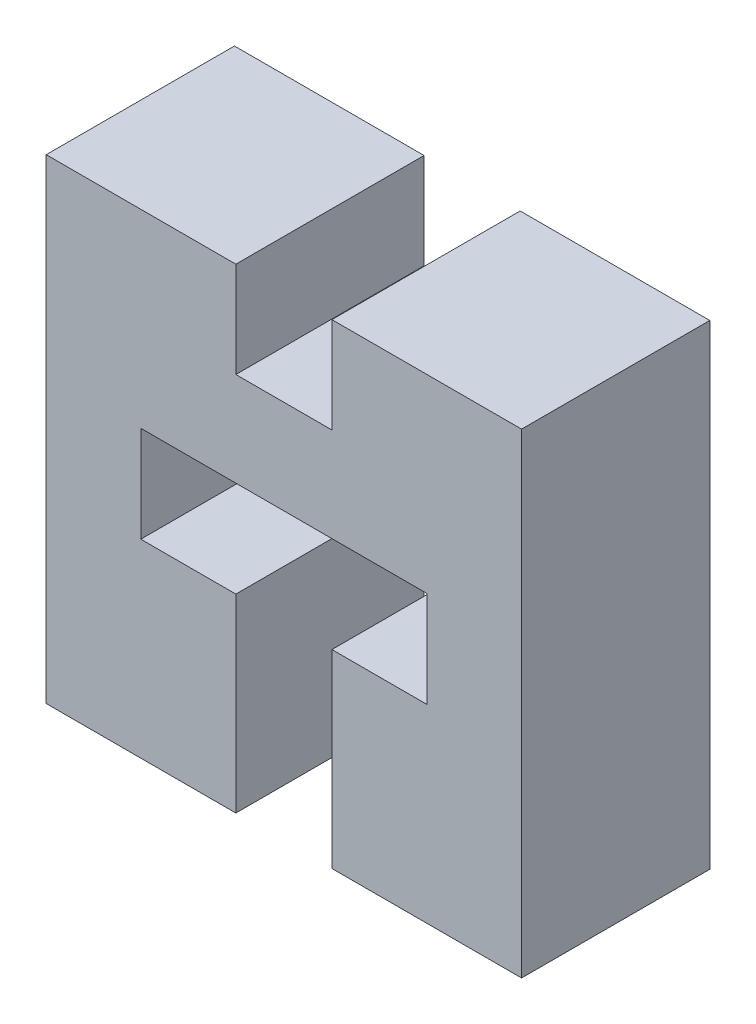
SolidWorks part; units mm, degrees
ref_plane "Front Plane" through (0, 0, 0) normal (0, 0, 1) x (1, 0, 0)
ref_plane "Top Plane" through (0, 0, 0) normal (0, 1, 0) x (1, 0, 0)
ref_plane "Right Plane" through (0, 0, 0) normal (1, 0, 0) x (0, 0, -1)
ref_plane "Plane1" through (0, 0, 9.9) normal (0, 0, 1) x (1, 0, 0)
sketch "Sketch1" plane through (0, 0, 9.9) normal (0, 0, 1) x (1, 0, 0)
  line L0 (14.974, 9.9735) -> (14.974, 15.0265)
  line L1 (14.974, 15.0265) -> (30.0265, 15.0265)
  line L2 (30.0265, 15.0265) -> (30.0265, 9.9735)
  line L3 (30.0265, 9.9735) -> (25.0265, 9.9735)
  line L4 (25.0265, 9.9735) -> (25.0265, 0)
  line L5 (25.0265, 0) -> (35, 0)
  line L6 (35, 0) -> (35, 25)
  line L7 (35, 25) -> (25.0265, 25)
  line L8 (25.0265, 25) -> (25.0265, 19.974)
  line L9 (25.0265, 19.974) -> (19.9735, 19.974)
  line L10 (19.9735, 19.974) -> (19.9735, 25)
  line L11 (19.9735, 25) -> (10, 25)
  line L12 (10, 25) -> (10, 0)
  line L13 (10, 0) -> (19.9735, 0)
  line L14 (19.9735, 0) -> (19.9735, 9.9735)
  line L15 (19.9735, 9.9735) -> (14.974, 9.9735)
  dimension "D1" = 25
extrude "Boss-Extrude1" add sketch "Sketch1" against normal blind 9.9
